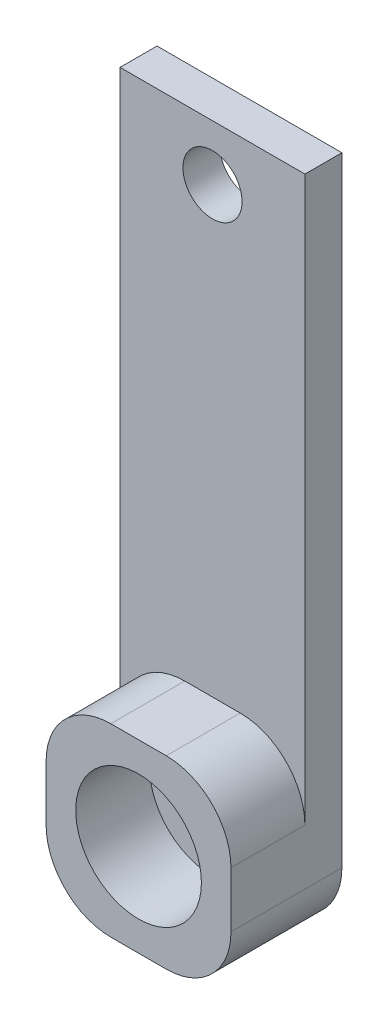
SolidWorks part; units mm, degrees
ref_plane "Front Plane" through (0, 0, 0) normal (0, 0, 1) x (1, 0, 0)
ref_plane "Top Plane" through (0, 0, 0) normal (0, 1, 0) x (1, 0, 0)
ref_plane "Right Plane" through (0, 0, 0) normal (1, 0, 0) x (0, 0, -1)
sketch "Sketch1" plane through (0, 0, 0) normal (0, 0, 1) x (1, 0, 0)
  line L1 (-17.8636, 28.6885) -> (-7.8636, 28.6885)
  line L2 (-17.8636, 28.6885) -> (-17.8636, -8.3115)
  line L3 (-17.8636, -8.3115) -> (-7.8636, -8.3115)
  line L4 (-7.8636, 28.6885) -> (-7.8636, -8.3115)
  dimension "D1" = 10
  dimension "D2" = 37
extrude "Boss-Extrude1" add sketch "Sketch1" along normal blind 2
sketch "Sketch2" plane through (0, 0, 2) normal (0, 0, 1) x (1, 0, 0)
  line L0 (-17.8636, 28.6885) -> (-17.8636, -8.3115) construction
  line L1 (-17.8636, 1.6885) -> (-7.8636, 1.6885)
  line L2 (-17.8636, 1.6885) -> (-17.8636, -8.3115)
  line L3 (-17.8636, -8.3115) -> (-7.8636, -8.3115)
  line L4 (-7.8636, 1.6885) -> (-7.8636, -8.3115)
  circle A0 centre (-12.8636, -3.3115) radius 3.4
  dimension "D1" = 6.8
  dimension "D2" = 5
  dimension "D3" = 5
extrude "Boss-Extrude2" add sketch "Sketch2" along normal blind 4
sketch "Sketch3" plane through (0, 0, 2) normal (0, 0, 1) x (1, 0, 0)
  line L3 (-7.8636, 28.6885) -> (-17.8636, 28.6885) construction
  line L4 (-7.8636, 1.6885) -> (-7.8636, 28.6885) construction
  circle A0 centre (-12.8636, 25.6885) radius 1.6
  dimension "D1" = 3.2
  dimension "D2" = 3
  dimension "D3" = 5
extrude "Cut-Extrude1" cut sketch "Sketch3" against normal blind 2
fillet "Fillet1" radius 3.5 4 edges at (-7.8636, -8.3115, 3) (-17.8636, -8.3115, 3)
sketch "Sketch4" plane through (0, 0, 2) normal (0, 0, 1) x (1, 0, 0)
  circle A0 centre (-12.8636, -3.3115) radius 1.5
  circle A1 centre (-12.8636, -3.3115) radius 3.4 construction
  dimension "D1" = 3
  dimension "D2" = 0
extrude "Cut-Extrude2" cut sketch "Sketch4" against normal blind 2
